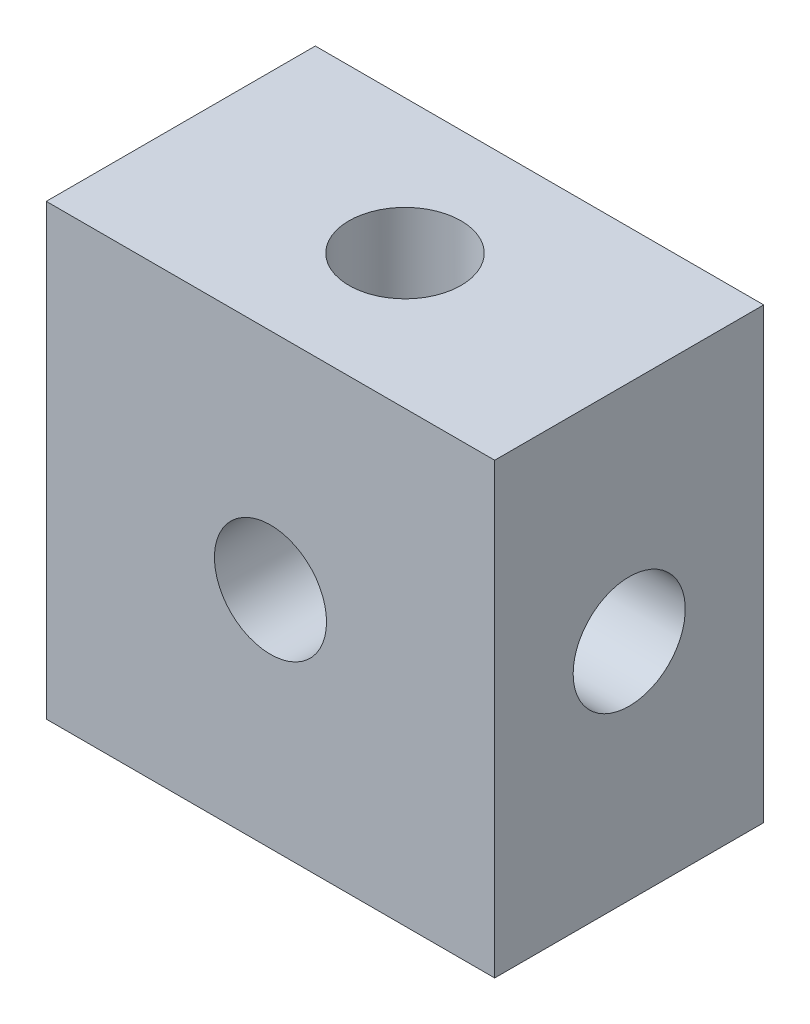
SolidWorks part; units mm, degrees
ref_plane "前视基准面" through (0, 0, 0) normal (0, 0, 1) x (1, 0, 0)
ref_plane "上视基准面" through (0, 0, 0) normal (0, 1, 0) x (1, 0, 0)
ref_plane "右视基准面" through (0, 0, 0) normal (1, 0, 0) x (0, 0, -1)
sketch "草图1" plane through (0, 0, 0) normal (0, 0, 1) x (1, 0, 0)
  line L1 (-5, -5) -> (5, -5)
  line L2 (-5, -5) -> (-5, 5)
  line L3 (-5, 5) -> (5, 5)
  line L4 (5, -5) -> (5, 5)
  line L5 (-5, -5) -> (5, 5) construction
  line L6 (-5, 5) -> (5, -5) construction
  point P0 (0, 0)
  dimension "D1" = 10
extrude "凸台-拉伸1" add sketch "草图1" along normal mid plane 6
sketch "草图2" plane through (0, 0, 3) normal (0, 0, 1) x (1, 0, 0)
  point P0 (0, 0)
sketch "草图3" plane through (0, -5, 0) normal (0, -1, 0) x (1, 0, 0)
  point P0 (0, 0)
sketch "草图4" plane through (-5, 0, 0) normal (-1, 0, 0) x (0, 0, 1)
  point P0 (0, 0)
hole_wizard "M3 螺纹孔1" positions "草图5" profile "草图6" tap size "M3" standard "GB" end condition through all
sketch "草图5" plane through (-5, 0, 0) normal (-1, 0, 0) x (0, 0, 1)
  point P0 (0, 0)
sketch "草图6" plane through (-5, 0, 0) normal (0, 1, 0) x (0, 0, 1)
  line L0 (0, 0) -> (0, 10)
  line L1 (0, 10) -> (1.25, 10)
  line L2 (1.25, 10) -> (1.25, 0)
  line L5 (1.25, 0) -> (0, 0)
  line L11 (0, -6.35) -> (0, 107.95) construction
  dimension "通孔螺纹孔钻头直径" = 2.5
  dimension "通孔螺纹孔钻头深度" = 10
cosmetic thread "孔螺蚊线1" parameters "D2"=3
hole_wizard "M3 螺纹孔2" positions "草图7" profile "草图8" tap size "M3" standard "GB" end condition through all
sketch "草图7" plane through (0, 0, 3) normal (0, 0, 1) x (1, 0, 0)
  point P0 (0, 0)
sketch "草图8" plane through (0, 0, 3) normal (1, 0, 0) x (0, -1, 0)
  line L0 (0, 0) -> (0, 6)
  line L1 (0, 6) -> (1.25, 6)
  line L2 (1.25, 6) -> (1.25, 0)
  line L5 (1.25, 0) -> (0, 0)
  line L11 (0, -6.35) -> (0, 107.95) construction
  dimension "通孔螺纹孔钻头直径" = 2.5
  dimension "通孔螺纹孔钻头深度" = 6
cosmetic thread "孔螺蚊线2" parameters "D2"=3
hole_wizard "M3 螺纹孔3" positions "草图9" profile "草图10" tap size "M3" standard "GB" end condition through all
sketch "草图9" plane through (0, -5, 0) normal (0, -1, 0) x (-1, 0, 0)
  point P0 (0, 0)
sketch "草图10" plane through (0, -5, 0) normal (1, 0, 0) x (0, 0, -1)
  line L0 (0, 0) -> (0, 10)
  line L1 (0, 10) -> (1.25, 10)
  line L2 (1.25, 10) -> (1.25, 0)
  line L5 (1.25, 0) -> (0, 0)
  line L11 (0, -6.35) -> (0, 107.95) construction
  dimension "通孔螺纹孔钻头直径" = 2.5
  dimension "通孔螺纹孔钻头深度" = 10
cosmetic thread "孔螺蚊线3" parameters "D2"=3
